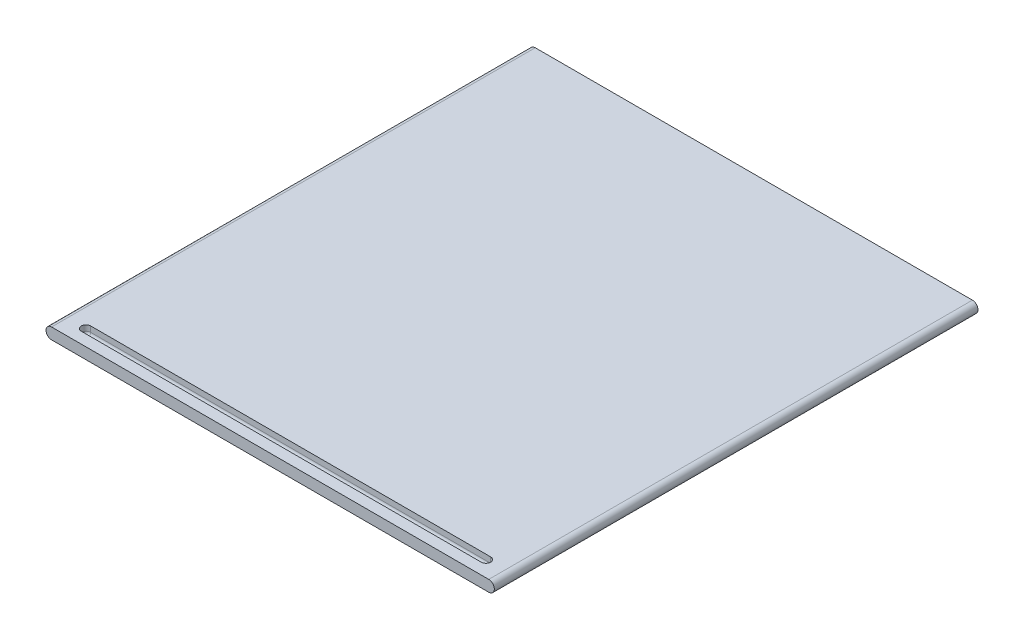
SolidWorks part; units mm, degrees
ref_plane "Ebene vorne" through (0, 0, 0) normal (0, 0, 1) x (1, 0, 0)
ref_plane "Ebene oben" through (0, 0, 0) normal (0, 1, 0) x (1, 0, 0)
ref_plane "Ebene rechts" through (0, 0, 0) normal (1, 0, 0) x (0, 0, -1)
sketch "Skizze1" plane through (0, 0, 0) normal (0, 0, 1) x (1, 0, 0)
  line L0 (-23.5, 0) -> (23.5, 0) construction
  line L1 (-23.5, 0.6) -> (23.5, 0.6)
  line L2 (-23.5, -0.6) -> (23.5, -0.6)
  arc A0 (-23.5, 0.6) -> (-23.5, -0.6) centre (-23.5, 0) ccw
  arc A1 (23.5, -0.6) -> (23.5, 0.6) centre (23.5, 0) ccw
  point P3 (0, 0)
  dimension "D1" = 47
  dimension "D2" = 1.2
extrude "Aufsatz-Linear austragen1" add sketch "Skizze1" along normal blind 52
sketch "Skizze2" plane through (0, 0.6, 0) normal (0, 1, 0) x (1, 0, 0)
  line L0 (-21.5, -50.3) -> (21.5, -50.3) construction
  line L1 (-21.5, -49.8) -> (21.5, -49.8)
  line L2 (-21.5, -50.8) -> (21.5, -50.8)
  line L3 (-23.5, -52) -> (-23.5, 0) construction
  line L4 (23.5, -52) -> (23.5, 0) construction
  line L5 (23.5, -52) -> (-23.5, -52) construction
  arc A0 (-21.5, -49.8) -> (-21.5, -50.8) centre (-21.5, -50.3) ccw
  arc A1 (21.5, -50.8) -> (21.5, -49.8) centre (21.5, -50.3) ccw
  point P2 (0, -50.3)
  dimension "D1" = 1
  dimension "D2" = 2
  dimension "D3" = 2
  dimension "D4" = 1.2
extrude "Schnitt-Linear austragen1" cut sketch "Skizze2" against normal blind 1
fillet "Verrundung2" radius 0.4 4 edges at (22, -0.4, 50.3) (0, -0.4, 50.8) (-22, -0.4, 50.3) (0, -0.4, 49.8)
